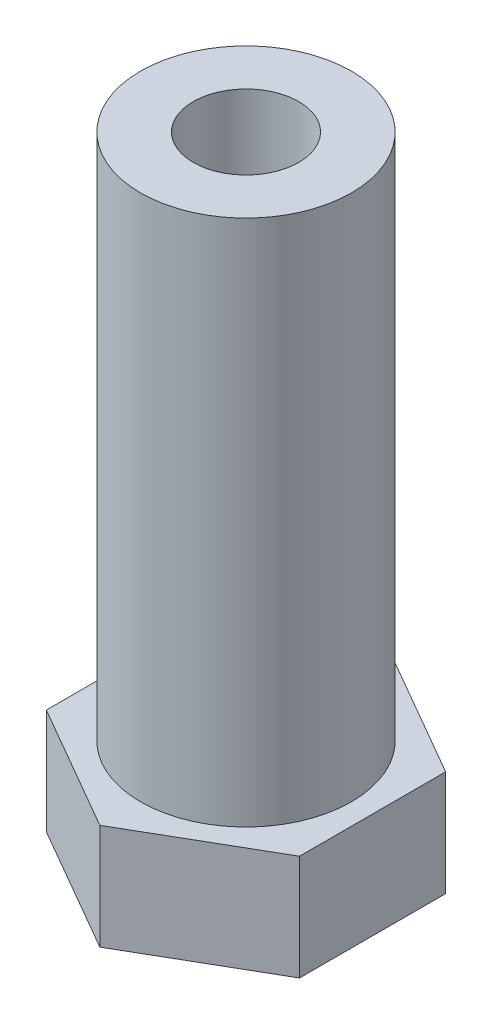
SolidWorks part; units mm, degrees
ref_plane "前视基准面" through (0, 0, 0) normal (0, 0, 1) x (1, 0, 0)
ref_plane "上视基准面" through (0, 0, 0) normal (0, 1, 0) x (1, 0, 0)
ref_plane "右视基准面" through (0, 0, 0) normal (1, 0, 0) x (0, 0, -1)
sketch "草图1" plane through (0, 0, 0) normal (0, 1, 0) x (1, 0, 0)
  line L1 (0, 6.9282) -> (-6, 3.4641)
  line L2 (-6, 3.4641) -> (-6, -3.4641)
  line L3 (-6, -3.4641) -> (0, -6.9282)
  line L4 (0, -6.9282) -> (6, -3.4641)
  line L5 (6, -3.4641) -> (6, 3.4641)
  line L6 (6, 3.4641) -> (0, 6.9282)
  circle A0 centre (0, 0) radius 6 construction
  circle A1 centre (0, 0) radius 2
  dimension "D2" = 4
  dimension "D1" = 12
extrude "凸台-拉伸1" add sketch "草图1" along normal blind 5
sketch "草图2" plane through (0, 5, 0) normal (0, 1, 0) x (1, 0, 0)
  circle A0 centre (0, 0) radius 2.5
  circle A1 centre (0, 0) radius 5
  dimension "D1" = 5
  dimension "D2" = 10
extrude "凸台-拉伸2" add sketch "草图2" along normal blind 25
